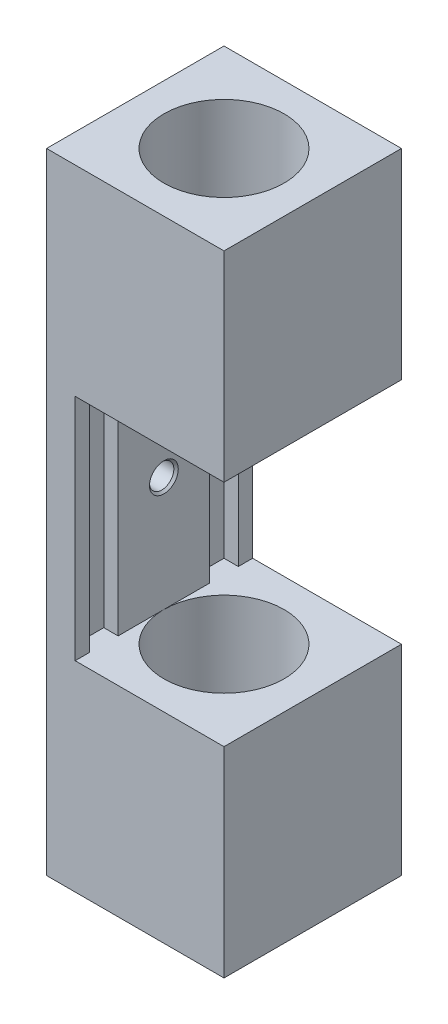
SolidWorks part; units mm, degrees
material "3.0205 (EN-AW 1200)"
ref_plane "前视基准面" through (0, 0, 0) normal (0, 0, 1) x (1, 0, 0)
ref_plane "上视基准面" through (0, 0, 0) normal (0, 1, 0) x (1, 0, 0)
ref_plane "右视基准面" through (0, 0, 0) normal (1, 0, 0) x (0, 0, -1)
other "Configuration Table"
sketch "草图2" plane through (0, 0, 0) normal (0, 1, 0) x (1, 0, 0)
  line L1 (-31, 31) -> (31, 31)
  line L2 (-31, 31) -> (-31, -31)
  line L3 (-31, -31) -> (31, -31)
  line L4 (31, 31) -> (31, -31)
  line L5 (-31, 31) -> (31, -31) construction
  line L6 (-31, -31) -> (31, 31) construction
  circle A0 centre (0, 0) radius 21
  dimension "D1" = 42
  dimension "D2" = 31
extrude "凸台-拉伸2" add sketch "草图2" along normal blind 220
ref_plane "基准面1" through (0, 110, 0) normal (0, 1, 0) x (1, 0, 0)
sketch "草图3" plane through (0, 110, 0) normal (0, 1, 0) x (1, 0, 0)
  line L0 (-21, 0) -> (-21, 36.7356)
  line L1 (-21, 36.7356) -> (47.2003, 36.7356)
  line L4 (47.2003, 36.7356) -> (47.2003, -37.1478)
  line L5 (47.2003, -37.1478) -> (-21, -37.1478)
  line L6 (-21, -37.1478) -> (-21, 0)
  circle A1 centre (0, 0) radius 21 construction
sketch "草图4" plane through (0, 0, 0) normal (0, -1, 0) x (1, 0, 0)
  circle A0 centre (0, 0) radius 21 construction
  circle A1 centre (0, 0) radius 21
  circle A2 centre (0, 0) radius 3.5
  dimension "D1" = 7
extrude "凸台-拉伸3" add sketch "草图4" against normal blind 5
extrude "切除-拉伸1" cut sketch "草图3" against normal mid plane 80
sketch "草图5" plane through (-21, 0, 0) normal (1, 0, 0) x (0, 0, -1)
  line L0 (34.1, 110) -> (-34.1, 110) construction
  circle A0 centre (0, 110) radius 5
  dimension "D1" = 10
hole_wizard "M10 螺纹孔1" positions "3D草图1" profile "草图6" tap size "M10" standard "KS" end condition through all
sketch3d "3D草图1"
  point P0 (-21, 110, 0)
cosmetic thread "孔螺蚊线1" parameters "D2"=10
sketch "草图6" plane through (-21, 110, 0) normal (0, 1, 0) x (0, 0, -1)
  line L0 (0, 0) -> (0, 10)
  line L1 (0, 10) -> (4.25, 10)
  line L2 (4.25, 10) -> (4.25, 0.775)
  line L3 (4.25, 0.775) -> (5.025, 0)
  line L5 (5.025, 0) -> (0, 0)
  line L6 (-4.25, 0.775) -> (-5.025, 0) construction
  line L11 (0, -6.35) -> (0, 107.95) construction
  dimension "通孔螺纹孔钻头直径" = 8.5
  dimension "通孔螺纹孔钻头深度" = 10
  dimension "近端锥形沉头孔直径" = 10.05
  dimension "近端锥形沉头孔角度" = 90
sketch "草图7" plane through (-21, 0, 0) normal (1, 0, 0) x (0, 0, -1)
  line L0 (16, 150) -> (16, 70)
  line L1 (31, 150) -> (0, 150) construction
  line L2 (-31, 0) -> (31, 0) construction
  line L3 (19.8743, 0) -> (27.6411, 0)
  line L4 (26, 70) -> (26, 150)
  line L5 (31, 150) -> (-31, 150) construction
  line L6 (26, 150) -> (16, 150)
  line L7 (31, 70) -> (0, 70) construction
  line L8 (26, 70) -> (16, 70)
  line L9 (31, 150) -> (31, 70) construction
  line M7 (0, 70) -> (31, 70)
  line M9 (31, 150) -> (0, 150)
  dimension "D1" = 5
  dimension "D2" = 10
extrude "切除-拉伸2" cut sketch "草图7" against normal blind 5 contours L4 L0 M7 M9
sketch "草图10" plane through (-21, 0, 0) normal (1, 0, 0) x (0, 0, -1)
  line L0 (-26, 150) -> (-26, 70)
  line L1 (0, 150) -> (-31, 150) construction
  line L2 (0, 70) -> (-31, 70) construction
  line L3 (-26, 70) -> (-16, 70)
  line L4 (31, 70) -> (-31, 70) construction
  line L5 (-16, 70) -> (-16, 150)
  line L6 (31, 150) -> (-31, 150) construction
  line L7 (-16, 150) -> (-26, 150)
  line L8 (-31, 70) -> (-31, 150) construction
  dimension "D1" = 10
  dimension "D2" = 5
extrude "切除-拉伸3" cut sketch "草图10" against normal blind 5
sketch "草图11" plane through (-21, 0, 0) normal (1, 0, 0) x (0, 0, -1)
  line L0 (-134.498, 110) -> (115.0744, 110)
  line L3 (34.1, 110) -> (-34.1, 110) construction
